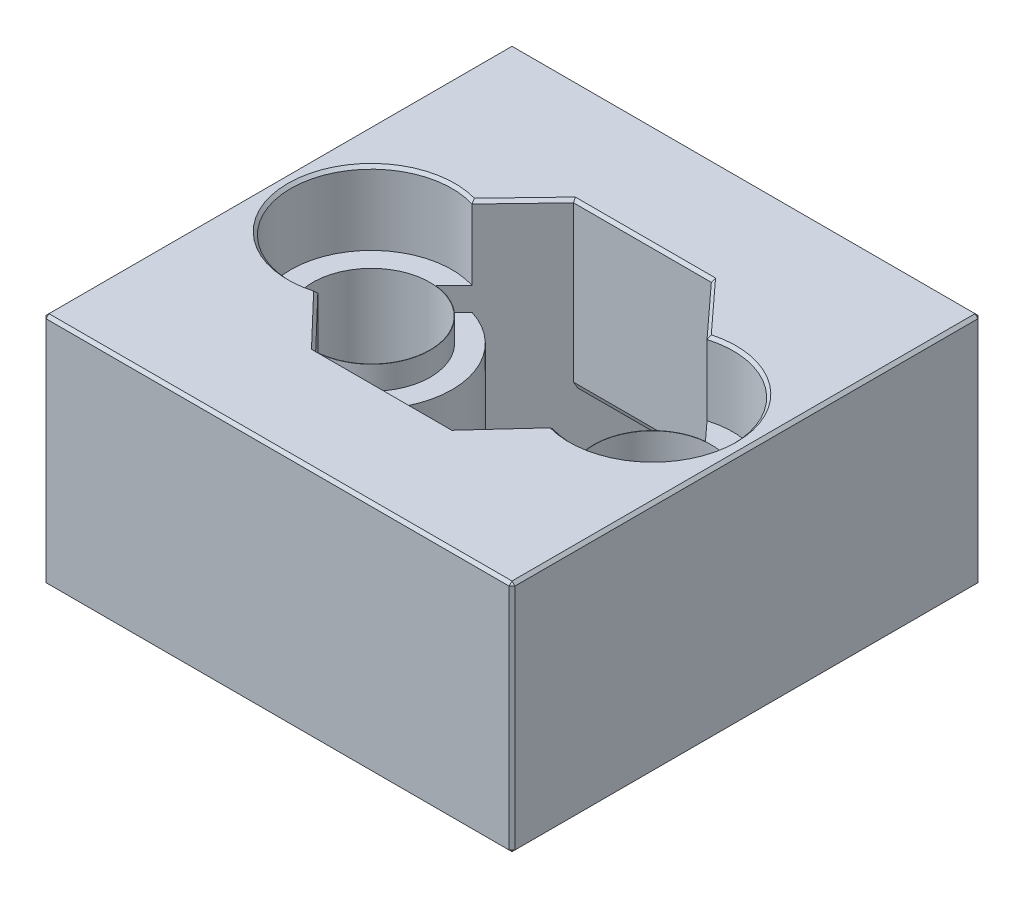
SolidWorks part; units mm, degrees
ref_plane "Front Plane" through (0, 0, 0) normal (0, 0, 1) x (1, 0, 0)
ref_plane "Top Plane" through (0, 0, 0) normal (0, 1, 0) x (1, 0, 0)
ref_plane "Right Plane" through (0, 0, 0) normal (1, 0, 0) x (0, 0, -1)
sketch "Sketch1" plane through (0, 0, 0) normal (0, 1, 0) x (1, 0, 0)
  line L1 (8, -8) -> (-8, -8)
  line L2 (8, -8) -> (8, 8)
  line L3 (8, 8) -> (-8, 8)
  line L4 (-8, -8) -> (-8, 8)
  line L5 (8, -8) -> (-8, 8) construction
  line L6 (8, 8) -> (-8, -8) construction
  line L24 (-4.624, -1.9749) -> (-2.324, -4.3749)
  line L25 (-2.324, -4.3749) -> (2.376, -4.3749)
  line L26 (2.376, -4.3749) -> (4.576, -1.9749)
  line L27 (4.576, 2.0251) -> (2.376, 4.4251)
  line L28 (2.376, 4.4251) -> (-2.324, 4.4251)
  line L29 (-2.324, 4.4251) -> (-4.6248, 2.0251)
  line L30 (-4.624, -1.9749) -> (-2.324, -4.3749)
  line L31 (-2.324, -4.3749) -> (2.376, -4.3749)
  line L32 (2.376, -4.3749) -> (4.576, -1.9749)
  line L33 (4.576, 2.0251) -> (2.376, 4.4251)
  line L34 (2.376, 4.4251) -> (-2.324, 4.4251)
  line L35 (-2.324, 4.4251) -> (-4.6248, 2.0251)
  arc A6 (4.576, 2.0251) -> (4.576, -1.9749) centre (4.776, 0.0251) ccw
  arc A7 (-4.624, -1.9749) -> (-4.6248, 2.0251) centre (-4.824, 0.0251) ccw
  arc A8 (4.576, 2.0251) -> (4.576, -1.9749) centre (4.776, 0.0251) ccw
  arc A9 (-4.624, -1.9749) -> (-4.6248, 2.0251) centre (-4.824, 0.0251) ccw
  point P0 (0, 0)
  dimension "D1" = 16
  dimension "D2" = 0
extrude "Boss-Extrude1" add sketch "Sketch1" against normal blind 8 contours A9 L30 L31 L32 A8 L33 L34 L35
sketch "Sketch2" plane through (0, 0, 0) normal (0, 1, 0) x (1, 0, 0)
  circle A0 centre (4.776, 0.0251) radius 2.75
  circle A1 centre (-4.824, 0.0251) radius 2.75
  point P7 (4.776, 0.0251)
  point P8 (-4.824, 0.0251)
  line M7 (-2.324, -4.3749) -> (-4.624, -1.9749)
  arc M8 (-4.624, -1.9749) -> (-4.6248, 2.0251) centre (-4.824, 0.0251) ccw
  line M9 (-4.6248, 2.0251) -> (-2.324, 4.4251)
  line M11 (2.376, 4.4251) -> (4.576, 2.0251)
  arc M12 (4.576, 2.0251) -> (4.576, -1.9749) centre (4.776, 0.0251) ccw
  line M13 (4.576, -1.9749) -> (2.376, -4.3749)
  dimension "D1" = 5.5
extrude "Boss-Extrude2" add sketch "Sketch2" against normal up to surface (4.7 mm away) from surface at -3.3 contours A0 M11 M13 M12 | A1 M7 M9 M8 up to face at (0, -8, 0)
hole_wizard "CBORE for M3 SHCS1" positions "Sketch7" profile "Sketch8" counterbore size "M3" standard "ANSI Metric" end condition through all
sketch "Sketch7" plane through (0, 0, 0) normal (0, 1, 0) x (1, 0, 0)
  point P0 (4.776, 0.0251)
  point P3 (-4.824, 0.0251)
sketch "Sketch8" plane through (4.776, 0, -0.0251) normal (1, 0, 0) x (0, 0, 1)
  line L0 (0, 0) -> (0, 8)
  line L1 (0, 8) -> (2, 8)
  line L3 (2, 8) -> (2, 2.5)
  line L4 (2, 2.5) -> (2.75, 2.5)
  line L5 (2.75, 2.5) -> (2.75, 0)
  line L7 (2.75, 0) -> (0, 0)
  line L11 (0, -6.35) -> (0, 107.95) construction
  dimension "Thru Hole Dia." = 4
  dimension "Thru Hole Depth" = 8
  dimension "C'Bore Dia." = 5.5
  dimension "C'Bore Depth" = 2.5
chamfer "WireClearance" distance 2.5 2 edges at (0.026, -8, -4.4251) (0.026, -8, 4.3749)
chamfer "Edgebreak-0.1" distance 0.1 28 edges at (3.1844, 0, -3.5431) (2.0386, -8, -4.7931) (3.1844, 0, 3.493) (2.0386, -8, 4.743) (-3.1722, 0, 3.4899) (-1.9743, -8, 4.7399) (-1.9741, -8, -4.7901) (-3.1724, 0, -3.5401) (-4.824, -8, 1.9749) (4.776, -8, 1.9749) (-8, 0, 0) (-8, -8, 0) (-8, -4, -8) (0, 0, -8) (0, -8, -8) (8, -4, -8) (8, 0, 0) (8, -8, 0) (8, -4, 8) (0, 0, 8) (0, -8, 8) (-8, -4, 8) (0.026, 0, -4.4251) (-7.574, 0, -0.0248) (0.026, 0, 4.3749) (7.526, 0, -0.0251) (0.026, -5.5, 4.3749) (0.026, -5.5, -4.4251)
